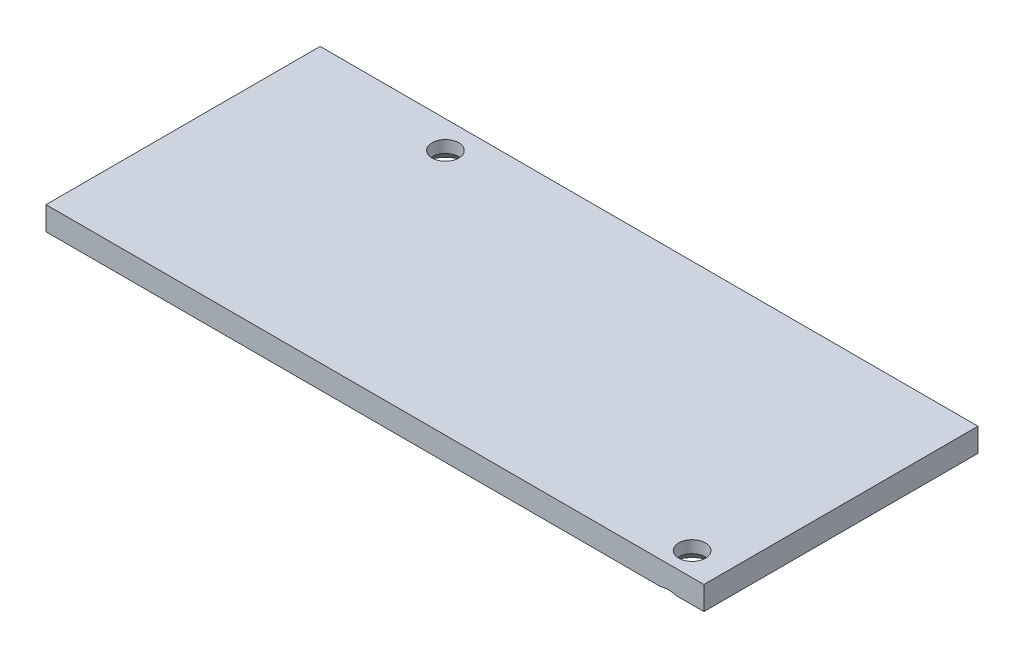
SolidWorks part; units mm, degrees
ref_plane "Front Plane" through (0, 0, 0) normal (0, 0, 1) x (1, 0, 0)
ref_plane "Top Plane" through (0, 0, 0) normal (0, 1, 0) x (1, 0, 0)
ref_plane "Right Plane" through (0, 0, 0) normal (1, 0, 0) x (0, 0, -1)
sketch "Sketch1" plane through (0, 0, 0) normal (0, 1, 0) x (1, 0, 0)
  line L1 (-42, -17.5) -> (42, -17.5)
  line L2 (-42, -17.5) -> (-42, 17.5)
  line L3 (-42, 17.5) -> (42, 17.5)
  line L4 (42, -17.5) -> (42, 17.5)
  line L5 (-42, -17.5) -> (42, 17.5) construction
  line L6 (-42, 17.5) -> (42, -17.5) construction
  point P0 (0, 0)
  dimension "D1" = 35
  dimension "D2" = 84
extrude "Boss-Extrude1" add sketch "Sketch1" along normal blind 3
hole_wizard "CSK for M3 Flat Head Machine Screw1" positions "Sketch4" profile "Sketch5" countersink size "M3" standard "ANSI Metric" end condition through all
sketch "Sketch4" plane through (0, 0, 0) normal (0, -1, 0) x (-1, 0, 0)
  point P0 (-37.5, -14.5)
  point P3 (22.5, 14)
sketch "Sketch5" plane through (37.5, 0, 14.5) normal (1, 0, 0) x (0, 0, -1)
  line L0 (0, 0) -> (0, 3)
  line L1 (0, 3) -> (1.7, 3)
  line L2 (1.7, 3) -> (1.7, 1.45)
  line L3 (1.7, 1.45) -> (3.15, 0)
  line L5 (3.15, 0) -> (0, 0)
  line L6 (-1.7, 1.45) -> (-3.15, 0) construction
  line L11 (0, -6.35) -> (0, 107.95) construction
  dimension "Thru Hole Dia." = 3.4
  dimension "Thru Hole Depth" = 3
  dimension "Near C'Sink Dia." = 6.3
  dimension "Near C'Sink Angle" = 90
